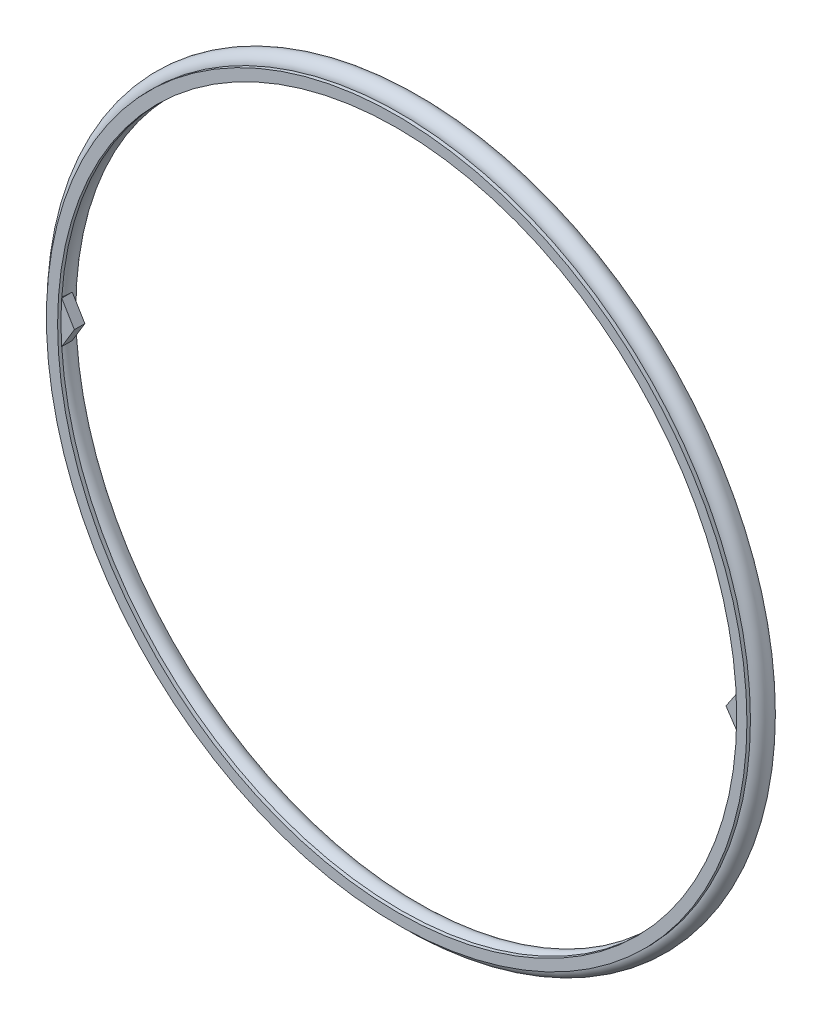
SolidWorks part; units mm, degrees
ref_plane "Front Plane" through (0, 0, 0) normal (0, 0, 1) x (1, 0, 0)
ref_plane "Top Plane" through (0, 0, 0) normal (0, 1, 0) x (1, 0, 0)
ref_plane "Right Plane" through (0, 0, 0) normal (1, 0, 0) x (0, 0, -1)
sketch "Sketch1" plane through (0, 0, 0) normal (0, 1, 0) x (1, 0, 0)
  line L0 (-99.949, 55.6597) -> (-99.949, -48.8973) construction
  circle A0 centre (0, 0) radius 2.921
  point P5 (-99.949, 55.6597)
  point P6 (-99.949, -48.8973)
  dimension "D1" = 5.842
  dimension "D2" = 99.949
revolve "Revolve1" add sketch "Sketch1" angle 360 about L0
sketch "Sketch2" plane through (0, 0, 0) normal (0, 0, 1) x (1, 0, 0)
  line L0 (-196.7917, 5.9939) -> (-193.176, 0)
  line L5 (-193.176, 0) -> (-196.7917, -5.9939)
  line L6 (-3.0951, 5.8096) -> (-7, 0)
  line L7 (-7, 0) -> (-3.0951, -5.8096)
  arc A1 (-196.7917, -5.9939) -> (-196.7917, 5.9939) centre (-193.176, 0) cw
  circle A2 centre (-99.949, 0) radius 97.028 construction
  arc A4 (-3.0951, 5.8096) -> (-3.0951, -5.8096) centre (-7, 0) cw
  dimension "D1" = 7
  dimension "D2" = 7
extrude "Boss-Extrude1" add sketch "Sketch2" along normal blind 3 separate body
sketch "Sketch5" plane through (0, 0, 3) normal (0, 0, 1) x (1, 0, 0)
  arc A0 (-200.176, 0) -> (0, 0) centre (-100.088, 0) cw
  arc A1 (-196.7917, 5.9939) -> (-196.7917, -5.9939) centre (-193.176, 0) ccw construction
  arc A2 (-200.176, 0) -> (0, 0) centre (-100.088, 0) ccw
extrude "Boss-Extrude2" add sketch "Sketch5" along normal blind 1
sketch "Sketch8" plane through (0, 0, 3) normal (0, 0, -1) x (-1, 0, 0)
  arc A0 (2.921, 0) -> (196.977, 0) centre (99.949, 0) cw
  circle A1 centre (99.949, 0) radius 97.028 construction
  arc A2 (2.921, 0) -> (196.977, 0) centre (99.949, 0) ccw
extrude "Cut-Extrude1" cut sketch "Sketch8" against normal blind 1
